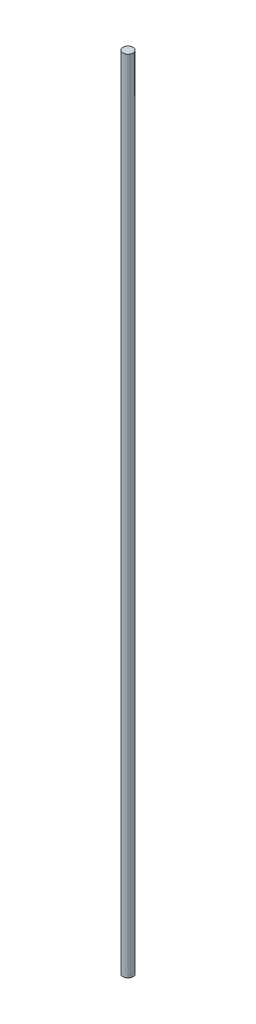
SolidWorks part; units mm, degrees
ref_plane "Front Plane" through (0, 0, 0) normal (0, 0, 1) x (1, 0, 0)
ref_plane "Top Plane" through (0, 0, 0) normal (0, 1, 0) x (1, 0, 0)
ref_plane "Right Plane" through (0, 0, 0) normal (1, 0, 0) x (0, 0, -1)
sketch "Sketch1" plane through (0, 0, 0) normal (0, 1, 0) x (1, 0, 0)
  circle A0 centre (0, 0) radius 3.175
  dimension "D1" = 6.35
extrude "Boss-Extrude1" add sketch "Sketch1" along normal blind 500
